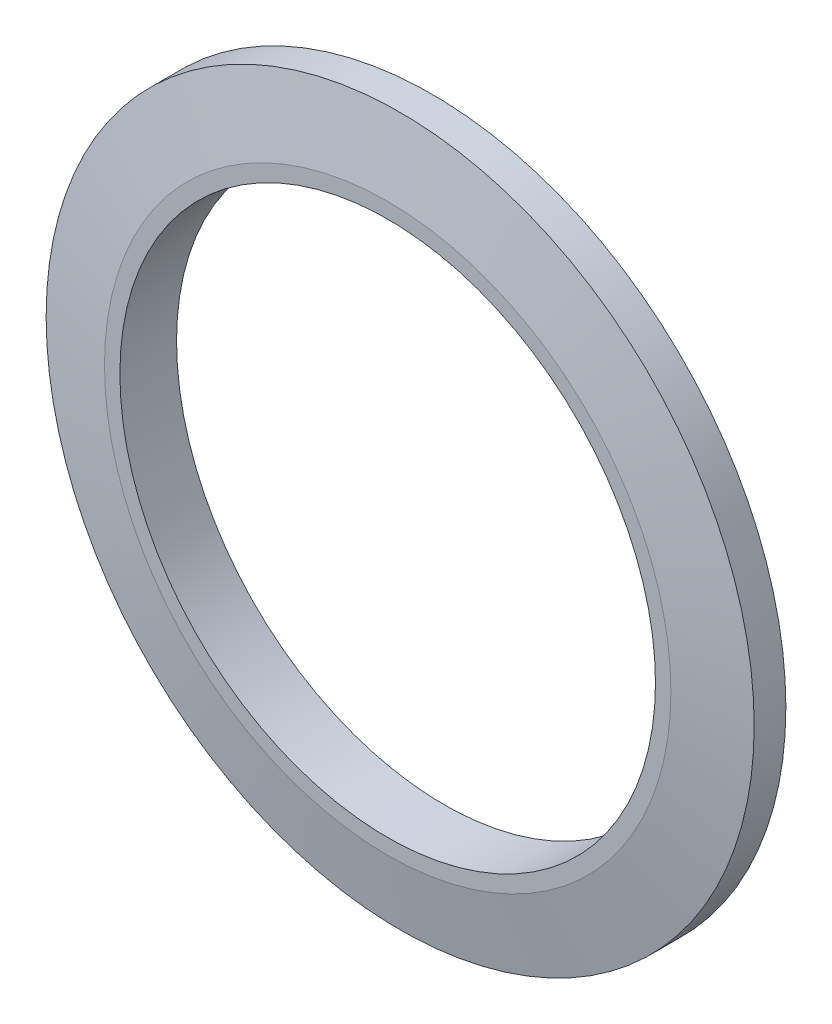
SolidWorks part; units mm, degrees
ref_plane "Front Plane" through (0, 0, 0) normal (0, 0, 1) x (1, 0, 0)
ref_plane "Top Plane" through (0, 0, 0) normal (0, 1, 0) x (1, 0, 0)
ref_plane "Right Plane" through (0, 0, 0) normal (1, 0, 0) x (0, 0, -1)
ref_axis "Axis1" through (0, 0, -0.1) along (0, 0, 1)
sketch "Sketch1" plane through (0, 0, 0) normal (0, 0, 1) x (1, 0, 0)
  circle A0 centre (0, 0) radius 12.5
extrude "Boss-Extrude1" add sketch "Sketch1" along normal blind 2 contours A0
sketch "Sketch2" plane through (0, 0, 2) normal (0, 0, 1) x (1, 0, 0)
  circle A0 centre (0, 0) radius 9.455
extrude "Cut-Extrude1" cut sketch "Sketch2" against normal blind 2
sketch "Sketch3" plane through (0, 0, 0) normal (1, 0, 0) x (0, 0, -1)
  line L2 (-2, 10) -> (-1.5592, 12.5)
  line L7 (-0.4408, 12.5) -> (0, 12.5)
  line L8 (0, 10) -> (-0.4408, 12.5)
  line L9 (-2, 10) -> (-2, 12.5)
  line L10 (-2, 12.5) -> (-1.5592, 12.5)
  line L11 (0, 12.5) -> (0, 10)
revolve "Cut-Revolve1" cut sketch "Sketch3" angle 360 about axis through (0, 0, -0.1) along (0, 0, 1)
